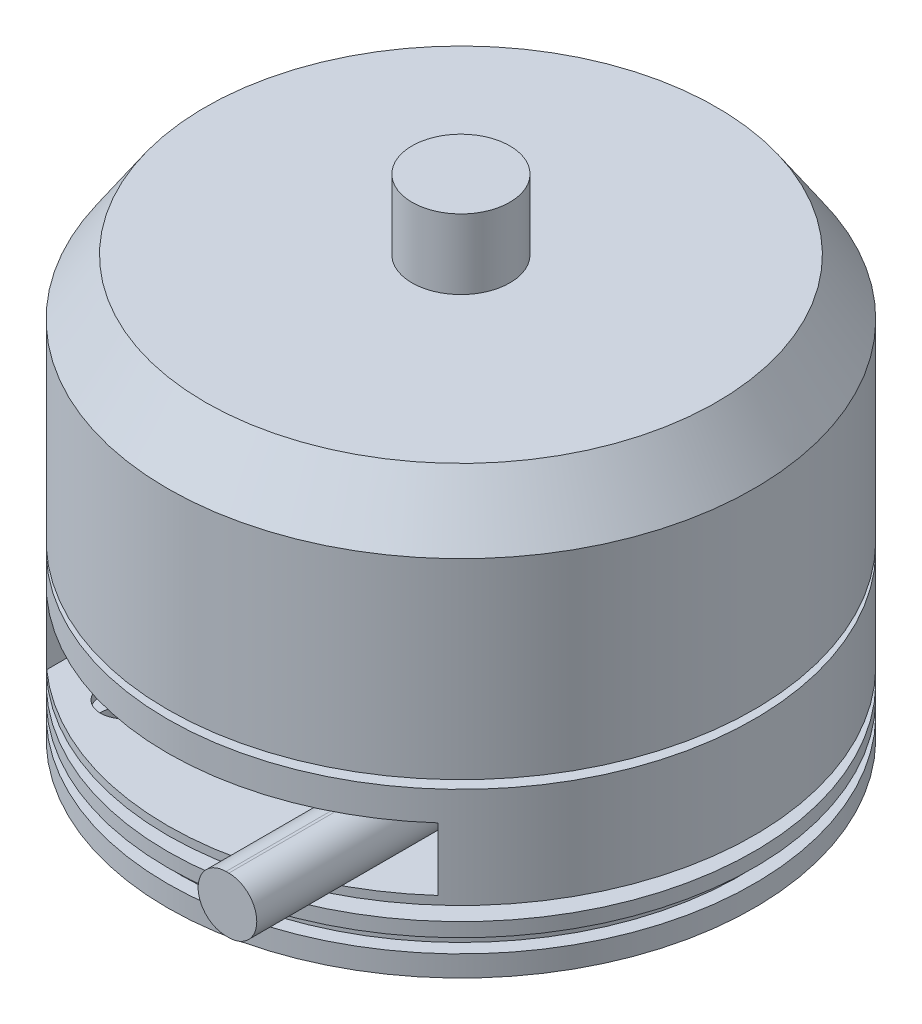
SolidWorks part; units mm, degrees
ref_plane "前视基准面" through (0, 0, 0) normal (0, 0, 1) x (1, 0, 0)
ref_plane "上视基准面" through (0, 0, 0) normal (0, 1, 0) x (1, 0, 0)
ref_plane "右视基准面" through (0, 0, 0) normal (1, 0, 0) x (0, 0, -1)
sketch "草图1" plane through (0, 0, 0) normal (0, 0, 1) x (1, 0, 0)
  line L0 (0, 0) -> (4.1, 0)
  line L1 (4.1, 0) -> (4.1, 6.7)
  line L2 (4.1, 6.7) -> (13.4, 6.7)
  line L3 (13.4, 6.7) -> (13.4, 8.7)
  line L4 (13.4, 8.7) -> (21, 8.7)
  line L5 (21, 8.7) -> (21, 10.2)
  line L6 (21, 10.2) -> (20, 10.2)
  line L7 (20, 10.2) -> (20, 11.2)
  line L8 (20, 11.2) -> (21, 11.2)
  line L9 (21, 11.2) -> (21, 12.2)
  line L10 (21, 12.2) -> (10, 12.2)
  line L11 (10, 12.2) -> (10, 13.2)
  line L12 (10, 13.2) -> (21, 13.2)
  line L13 (21, 13.2) -> (21, 20.4)
  line L14 (21, 20.4) -> (5, 20.4)
  line L15 (5, 20.4) -> (5, 21)
  line L16 (5, 21) -> (21, 21)
  line L17 (21, 21) -> (21, 34.7)
  line L18 (21, 34.7) -> (18.3, 38.7)
  line L19 (18.3, 38.7) -> (3.5, 38.7)
  line L20 (3.5, 38.7) -> (3.5, 43.7)
  line L21 (3.5, 43.7) -> (0, 43.7)
  line L22 (0, 43.7) -> (0, 0) construction
  line L23 (0, 0) -> (0, 43.7)
  dimension "D1" = 8.2
  dimension "D2" = 26.8
  dimension "D3" = 42
  dimension "D4" = 10
  dimension "D5" = 1.5
  dimension "D6" = 1
  dimension "D7" = 1
  dimension "D8" = 20
  dimension "D9" = 1
  dimension "D10" = 7.2
  dimension "D11" = 0.6
  dimension "D12" = 13.7
  dimension "D13" = 5
  dimension "D14" = 2
  dimension "D15" = 6.7
  dimension "D16" = 1
  dimension "D17" = 7
  dimension "D18" = 36.6
  dimension "D19" = 4
  dimension "D20" = 30
revolve "旋转1" add sketch "草图1" angle 360 about L22
ref_plane "基准面1" through (0, 0, 21) normal (0, 0, 1) x (1, 0, 0)
sketch "草图2" plane through (0, 0, 21) normal (0, 0, 1) x (1, 0, 0)
  line L1 (-14, 18.3) -> (14, 18.3)
  line L2 (-14, 18.3) -> (-14, 13.8)
  line L3 (-14, 13.8) -> (14, 13.8)
  line L4 (14, 18.3) -> (14, 13.8)
  line L5 (-14, 18.3) -> (14, 13.8) construction
  line L6 (-14, 13.8) -> (14, 18.3) construction
  line L7 (-21, 13.2) -> (21, 13.2) construction
  point P0 (0, 16.05)
  dimension "D1" = 28
  dimension "D2" = 4.5
  dimension "D3" = 0.6
extrude "切除-拉伸1" cut sketch "草图2" against normal blind 10
sketch "草图3" plane through (0, 0, 11) normal (0, 0, 1) x (1, 0, 0)
  line L0 (9.1851, 16.0532) -> (9.3851, 16.0532) construction
  line L1 (9.1851, 18.0532) -> (9.3851, 18.0532)
  line L2 (9.1851, 14.0532) -> (9.3851, 14.0532)
  arc A0 (9.1851, 18.0532) -> (9.1851, 14.0532) centre (9.1851, 16.0532) ccw
  arc A1 (9.3851, 14.0532) -> (9.3851, 18.0532) centre (9.3851, 16.0532) ccw
  point P2 (9.2851, 16.0532)
  dimension "D1" = 4
  dimension "D2" = 0.2
extrude "凸台-拉伸1" add sketch "草图3" along normal blind 15
sketch "草图7" plane through (0, 8.7, 0) normal (0, -1, 0) x (1, 0, 0)
  line L0 (-9.3687, 14.781) -> (9.3687, -14.781) construction
  line L1 (14.781, 9.3687) -> (-14.781, -9.3687) construction
  circle A0 centre (-9.3687, 14.781) radius 1.5
  circle A1 centre (-14.781, -9.3687) radius 1.5
  circle A2 centre (14.781, 9.3687) radius 1.5
  circle A3 centre (9.3687, -14.781) radius 1.5
  circle A4 centre (0, 0) radius 17.5 construction
  dimension "D2" = 35
  dimension "D1" = 3
hole_wizard "M4 螺纹孔2" positions "3D草图2" profile "草图10" tap size "M4" standard "GB"
sketch3d "3D草图2"
  point P0 (-14.781, 8.7, -9.3687)
  point P3 (-9.3687, 8.7, 14.781)
  point P6 (9.3687, 8.7, -14.781)
  point P9 (14.781, 8.7, 9.3687)
sketch "草图10" plane through (-14.781, 8.7, -9.3687) normal (1, 0, 0) x (0, 0, -1)
  line L0 (0, 0) -> (0, 11.4914)
  line L1 (0, 11.4914) -> (1.65, 10.5)
  line L2 (1.65, 10.5) -> (1.65, 0)
  line L5 (1.65, 0) -> (0, 0)
  line L10 (0, 11.4914) -> (-1.65, 10.5) construction
  line L11 (0, -6.35) -> (0, 107.95) construction
  dimension "螺纹孔钻头直径" = 3.3
  dimension "螺纹孔钻头深度" = 10.5
  dimension "导头角度" = 118
cosmetic thread "孔螺蚊线6" parameters "D1"=8, "D2"=4
cosmetic thread "孔螺蚊线7" parameters "D1"=8, "D2"=4
cosmetic thread "孔螺蚊线8" parameters "D1"=8, "D2"=4
cosmetic thread "孔螺蚊线9" parameters "D1"=8, "D2"=4
sketch "草图11" plane through (0, 0, 0) normal (0, 0, 1) x (1, 0, 0)
  line L0 (0, 0) -> (0, 44.727) construction
